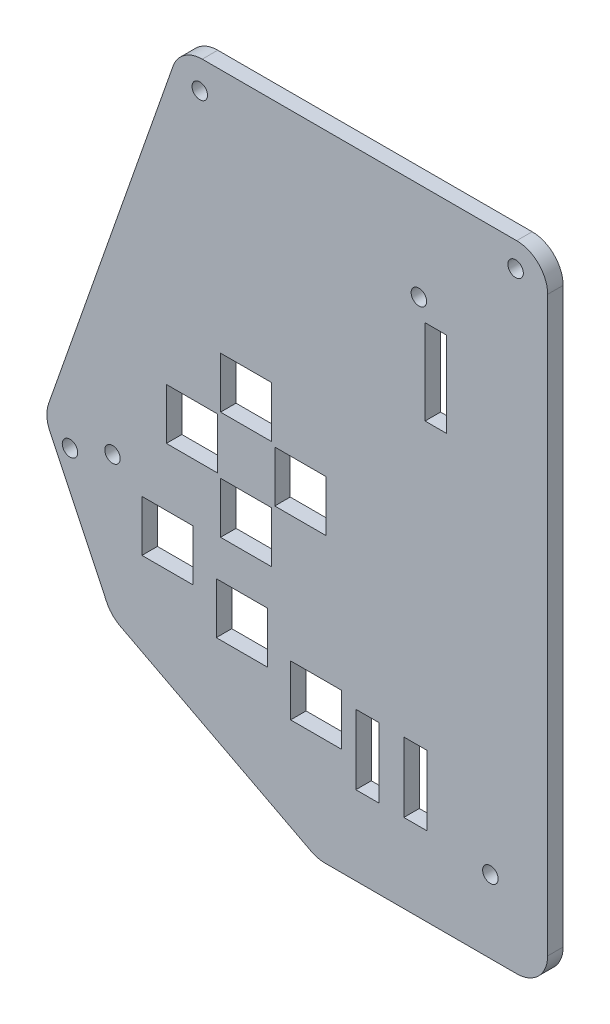
SolidWorks part; units mm, degrees
ref_plane "Front Plane" through (0, 0, 0) normal (0, 0, 1) x (1, 0, 0)
ref_plane "Top Plane" through (0, 0, 0) normal (0, 1, 0) x (1, 0, 0)
ref_plane "Right Plane" through (0, 0, 0) normal (1, 0, 0) x (0, 0, -1)
sketch "Sketch1" plane through (0, 0, 0) normal (0, 0, 1) x (1, 0, 0)
  line L6 (-20.066, -57.15) -> (46.99, -57.15) construction
  line L7 (-12.446, -73.152) -> (46.99, -73.152) construction
  line L8 (-3.3141, 6.35) -> (48.26, 6.35)
  line L9 (53.34, 1.27) -> (53.34, -92.71)
  line L10 (48.26, -97.79) -> (16.847, -97.79)
  line L16 (-8.1072, 2.9529) -> (-28.5162, -55.1739)
  line L18 (-20.066, -57.15) -> (-29.21, -57.15) construction
  line L26 (0, 0) -> (46.99, 0) construction
  line L27 (46.99, 0) -> (46.99, -88.9) construction
  line L28 (46.99, -88.9) -> (17.78, -88.9) construction
  line L29 (17.78, -88.9) -> (-12.446, -73.152) construction
  line L30 (-12.446, -73.152) -> (-20.066, -57.15) construction
  line L31 (-20.066, -57.15) -> (0, 0) construction
  line L32 (46.99, -57.15) -> (46.99, -88.9) construction
  line L33 (17.78, -88.9) -> (15.603, -97.79) construction
  line L34 (-12.446, -73.152) -> (-17.9301, -78.4424) construction
  line L35 (14.4997, -97.2152) -> (-16.7505, -80.9336)
  line L36 (-28.3096, -59.0409) -> (-18.9898, -78.6124)
  arc A0 (53.34, -92.71) -> (48.26, -97.79) centre (48.26, -92.71) cw
  arc A1 (14.4997, -97.2152) -> (16.847, -97.79) centre (16.847, -92.71) ccw
  arc A2 (-16.7505, -80.9336) -> (-18.9898, -78.6124) centre (-14.4033, -76.4284) cw
  arc A3 (-28.5162, -55.1739) -> (-28.3096, -59.0409) centre (-23.723, -56.8568) ccw
  arc A4 (-8.1072, 2.9529) -> (-3.3141, 6.35) centre (-3.3141, 1.27) cw
  arc A5 (48.26, 6.35) -> (53.34, 1.27) centre (48.26, 1.27) cw
  point P13 (53.34, -97.79)
  point P32 (53.34, 6.35)
  dimension "D8" = 5.08
  dimension "D1" = 88.9
  dimension "D2" = 29.21
  dimension "D3" = 59.436
  dimension "D4" = 67.056
  dimension "D5" = 104.14
  dimension "D6" = 82.55
  dimension "D7" = 46.99
  dimension "D13" = 103.76
  dimension "D17" = 108.51
sketch "Sketch3" plane through (0, 0, 0) normal (0, 0, 1) x (1, 0, 0)
  line L6 (-20.066, -57.15) -> (46.99, -57.15) construction
  line L7 (-12.446, -73.152) -> (46.99, -73.152) construction
  line L8 (0, 0) -> (46.99, 0) construction
  line L9 (46.99, 0) -> (46.99, -88.9) construction
  line L10 (46.99, -88.9) -> (17.78, -88.9) construction
  line L11 (17.78, -88.9) -> (-12.446, -73.152) construction
  line L12 (-12.446, -73.152) -> (-20.066, -57.15) construction
  line L13 (-20.066, -57.15) -> (0, 0) construction
  line L14 (3.8784, -55.88) -> (3.8784, -38.1) construction
  circle A0 centre (3.8784, -38.1) radius 5.08
  circle A1 centre (-5.0116, -46.99) radius 5.08
  circle A2 centre (3.8784, -55.88) radius 5.08
  circle A3 centre (12.7684, -46.99) radius 5.08
  circle A4 centre (-9.144, -65.024) radius 5.08
  circle A5 centre (3.048, -70.612) radius 5.08
  circle A6 centre (15.24, -76.2) radius 5.08
  dimension "D7" = 10.16
  dimension "D1" = 43.1116
  dimension "D2" = 8.89
  dimension "D3" = 8.89
  dimension "D4" = 46.99
  dimension "D5" = 8.89
  dimension "D6" = 8.89
  dimension "D8" = 12.192
  dimension "D9" = 5.588
  dimension "D10" = 5.588
  dimension "D11" = 12.192
  dimension "D12" = 43.942
  dimension "D13" = 70.612
sketch "Sketch10" plane through (0, 0, 0) normal (0, 0, 1) x (1, 0, 0)
  line L1 (53.34, 1.27) -> (53.34, -92.71)
  line L6 (48.26, -97.79) -> (16.847, -97.79)
  line L16 (-8.1072, 2.9529) -> (-28.5162, -55.1739)
  line L19 (53.34, 1.27) -> (53.34, -92.71) construction
  line L21 (-8.1072, 2.9529) -> (-28.5162, -55.1739) construction
  line L24 (14.4997, -97.2152) -> (-16.7505, -80.9336)
  line L25 (-18.9898, -78.6124) -> (-28.3096, -59.0409)
  line L26 (-3.3141, 6.35) -> (48.26, 6.35)
  arc A0 (-18.9898, -78.6124) -> (-16.7505, -80.9336) centre (-14.4033, -76.4284) ccw
  arc A1 (16.847, -97.79) -> (14.4997, -97.2152) centre (16.847, -92.71) cw
  arc A2 (-28.5162, -55.1739) -> (-28.3096, -59.0409) centre (-23.723, -56.8568) ccw
  arc A3 (53.34, -92.71) -> (48.26, -97.79) centre (48.26, -92.71) cw
  arc A4 (-8.1072, 2.9529) -> (-3.3141, 6.35) centre (-3.3141, 1.27) cw
  arc A5 (48.26, 6.35) -> (53.34, 1.27) centre (48.26, 1.27) cw
  point P13 (15.603, -97.79)
  point P17 (-29.21, -57.15)
  point P20 (53.34, -97.79)
  dimension "D1" = 5.08
extrude "Boss-Extrude1" add sketch "Sketch10" along normal blind 2.54
sketch "Sketch11" plane through (0, 0, 2.54) normal (0, 0, 1) x (1, 0, 0)
  line L0 (46.99, -88.9) -> (17.78, -88.9) construction
  line L5 (33.561, -73.406) -> (29.751, -73.406)
  line L6 (33.561, -73.406) -> (33.561, -84.836)
  line L11 (33.561, -84.836) -> (29.751, -84.836)
  line L12 (29.751, -73.406) -> (29.751, -84.836)
  line L18 (46.99, 0) -> (46.99, -88.9) construction
  line L23 (25.687, -73.406) -> (21.877, -73.406)
  line L24 (25.687, -73.406) -> (25.687, -84.836)
  line L29 (25.687, -84.836) -> (21.877, -84.836)
  line L30 (21.877, -73.406) -> (21.877, -84.836)
  line L42 (8.0694, -51.689) -> (-0.3126, -51.689)
  line L43 (8.0694, -51.689) -> (8.0694, -60.071)
  line L44 (8.0694, -60.071) -> (-0.3126, -60.071)
  line L45 (-0.3126, -51.689) -> (-0.3126, -60.071)
  line L46 (-0.8206, -42.799) -> (-9.2026, -42.799)
  line L47 (-0.8206, -42.799) -> (-0.8206, -51.181)
  line L48 (-0.8206, -51.181) -> (-9.2026, -51.181)
  line L49 (-9.2026, -42.799) -> (-9.2026, -51.181)
  line L52 (8.0694, -42.291) -> (-0.3126, -42.291)
  line L53 (-0.3126, -33.909) -> (-0.3126, -42.291)
  line L54 (16.9594, -42.799) -> (8.5774, -42.799)
  line L55 (16.9594, -42.799) -> (16.9594, -51.181)
  line L56 (16.9594, -51.181) -> (8.5774, -51.181)
  line L57 (8.5774, -42.799) -> (8.5774, -51.181)
  line L58 (-0.3126, -33.909) -> (8.0694, -33.909)
  line L59 (8.0694, -33.909) -> (8.0694, -42.291)
  line L60 (3.8784, -51.689) -> (3.8784, -60.071) construction
  line L61 (-0.3126, -55.88) -> (8.0694, -55.88) construction
  line L62 (-5.0116, -51.181) -> (-5.0116, -42.799) construction
  line L63 (-9.2026, -46.99) -> (-0.8206, -46.99) construction
  line L64 (12.7684, -42.799) -> (12.7684, -51.181) construction
  line L65 (8.5774, -46.99) -> (16.9594, -46.99) construction
  line L66 (3.8784, -33.909) -> (3.8784, -42.291) construction
  line L67 (-0.3126, -38.1) -> (8.0694, -38.1) construction
  line L68 (-4.826, -60.706) -> (-4.826, -69.088)
  line L69 (-13.208, -65.024) -> (-5.08, -65.024) construction
  line L70 (-9.144, -60.96) -> (-9.144, -69.088) construction
  line L71 (-4.826, -69.088) -> (-13.208, -69.088)
  line L72 (-13.208, -60.706) -> (-13.208, -69.088)
  line L73 (-4.826, -60.706) -> (-13.208, -60.706)
  line L74 (7.366, -66.294) -> (7.366, -74.676)
  line L75 (-1.016, -70.612) -> (7.112, -70.612) construction
  line L76 (3.048, -66.548) -> (3.048, -74.676) construction
  line L77 (7.366, -74.676) -> (-1.016, -74.676)
  line L78 (-1.016, -66.294) -> (-1.016, -74.676)
  line L79 (7.366, -66.294) -> (-1.016, -66.294)
  line L80 (19.558, -71.882) -> (19.558, -80.264)
  line L81 (11.176, -76.2) -> (19.304, -76.2) construction
  line L82 (15.24, -72.136) -> (15.24, -80.264) construction
  line L83 (19.558, -80.264) -> (11.176, -80.264)
  line L84 (11.176, -71.882) -> (11.176, -80.264)
  line L85 (19.558, -71.882) -> (11.176, -71.882)
  dimension "D1" = 4.064
  dimension "D3" = 13.429
  dimension "D4" = 11.43
  dimension "D5" = 3.81
  dimension "D6" = 4.064
  dimension "D7" = 11.43
  dimension "D8" = 4.064
  dimension "D9" = 3.81
  dimension "D10" = 2.319
  dimension "D11" = 3.81
  dimension "D12" = 6.223
  dimension "D13" = 3.81
  dimension "D14" = 5.588
  dimension "D15" = 8.382
  dimension "D16" = 2.794
  dimension "D17" = 0.508
  dimension "D18" = 0.508
  dimension "D21" = 8.382
  dimension "D22" = 8.382
extrude "Cut-Extrude1" cut sketch "Sketch11" against normal through all both and the other way through all
sketch "Sketch12" plane through (0, 0, 0) normal (0, 0, -1) x (-1, 0, 0)
  line L0 (20.066, -57.15) -> (-46.99, -57.15) construction
  line L2 (-46.99, 0) -> (-46.99, -88.9) construction
  line L5 (18.034, -57.15) -> (20.066, -57.15) construction
  line L10 (-46.99, -88.9) -> (-17.78, -88.9) construction
  circle A2 centre (18.034, -57.15) radius 1.27
  circle A3 centre (-43.942, -85.852) radius 1.27
  dimension "D1" = 2.54
  dimension "D6" = 2.032
  dimension "D11" = 3.048
  dimension "D12" = 3.048
extrude "Cut-Extrude2" cut sketch "Sketch12" against normal through all both and the other way through all
sketch "Sketch13" plane through (0, 0, 0) normal (0, 0, -1) x (-1, 0, 0)
  line L0 (28.3096, -59.0409) -> (18.9898, -78.6124) construction
  line L1 (8.1072, 2.9529) -> (28.5162, -55.1739) construction
  line L2 (3.3141, 6.35) -> (-48.26, 6.35) construction
  line L4 (-53.34, 1.27) -> (-53.34, -92.71) construction
  circle A1 centre (25.0123, -59.762) radius 1.27
  circle A4 centre (-48.0822, 2.286) radius 1.27
  circle A5 centre (3.7187, 1.651) radius 1.27
  dimension "D1" = 2.54
  dimension "D2" = 4.826
  dimension "D4" = 4.064
  dimension "D3" = 2.667
  dimension "D5" = 5.2578
  dimension "D6" = 4.699
  dimension "D7" = 4.572
extrude "Cut-Extrude3" cut sketch "Sketch13" against normal through all both and the other way through all
sketch "Sketch14" plane through (0, 0, 0) normal (0, 0, -1) x (-1, 0, 0)
  line L0 (-36.7885, -26.7831) -> (-33.2325, -26.7831)
  line L1 (-36.7885, -12.8131) -> (-36.7885, -26.7831)
  line L2 (-33.2325, -12.8131) -> (-36.7885, -12.8131)
  line L3 (-33.2325, -12.8131) -> (-33.2325, -26.7831)
  line L4 (-53.34, 1.27) -> (-53.34, -92.71) construction
  line L5 (3.3141, 6.35) -> (-48.26, 6.35) construction
  dimension "D1" = 16.5515
  dimension "D2" = 13.97
  dimension "D3" = 19.1631
  dimension "D4" = 3.556
extrude "Cut-Extrude4" cut sketch "Sketch14" against normal through all both and the other way through all
sketch "Sketch16" plane through (0, 0, 0) normal (0, 0, -1) x (-1, 0, 0)
  line L0 (3.3141, 6.35) -> (-48.26, 6.35) construction
  line L1 (-53.34, 1.27) -> (-53.34, -92.71) construction
  circle A0 centre (-32.219, -9.6761) radius 1.27
  dimension "D1" = 16.0261
  dimension "D2" = 2.54
  dimension "D3" = 21.121
extrude "Cut-Extrude5" cut sketch "Sketch16" against normal through all both and the other way through all
